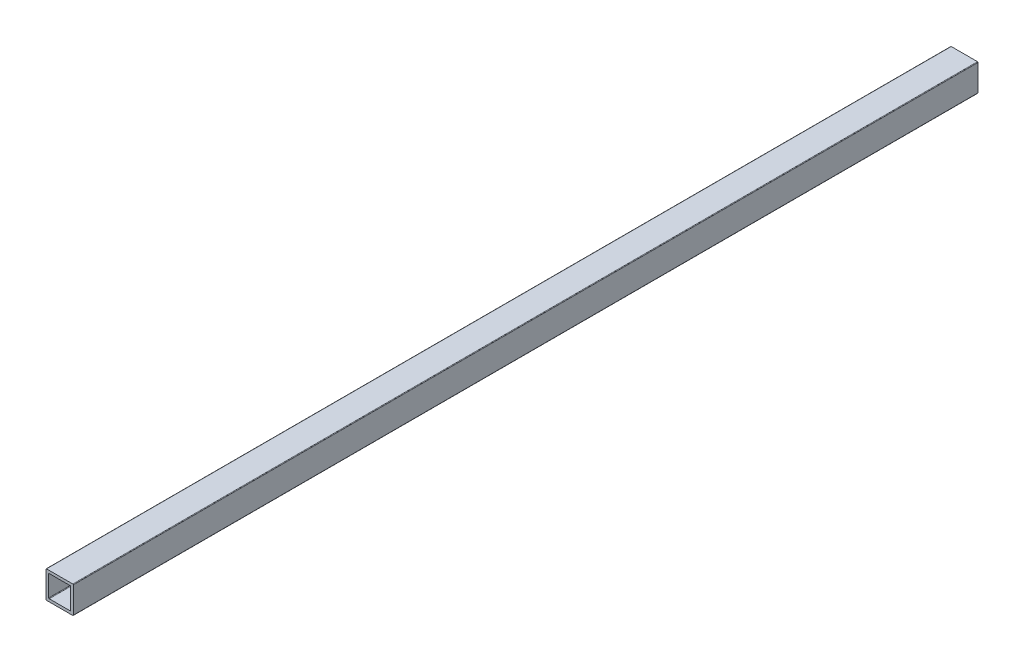
SolidWorks part; units mm, degrees
ref_plane "前基準面" through (0, 0, 0) normal (0, 0, 1) x (1, 0, 0)
ref_plane "上基準面" through (0, 0, 0) normal (0, 1, 0) x (1, 0, 0)
ref_plane "右基準面" through (0, 0, 0) normal (1, 0, 0) x (0, 0, -1)
sketch "草圖1" plane through (0, 0, 0) normal (0, 0, 1) x (1, 0, 0)
  line L1 (-5, 5) -> (5, 5)
  line L2 (-5, 5) -> (-5, -5)
  line L3 (-5, -5) -> (5, -5)
  line L4 (5, 5) -> (5, -5)
  line L5 (-4, 4) -> (4, 4)
  line L6 (-4, 4) -> (-4, -4)
  line L7 (-4, -4) -> (4, -4)
  line L8 (4, 4) -> (4, -4)
  dimension "D1" = 10
  dimension "D2" = 5
  dimension "D3" = 10
  dimension "D4" = 5
  dimension "D5" = 1
  dimension "D6" = 1
  dimension "D7" = 1
  dimension "D8" = 1
extrude "填料-伸長1" add sketch "草圖1" along normal blind 331.47
fillet "圓角1" radius 0.2 8 edges at (4, 4, 165.735) (-4, 4, 165.735) (-5, -5, 165.735) (4, -4, 165.735) (5, -5, 165.735) (-5, 5, 165.735) (-4, -4, 165.735) (5, 5, 165.735)
